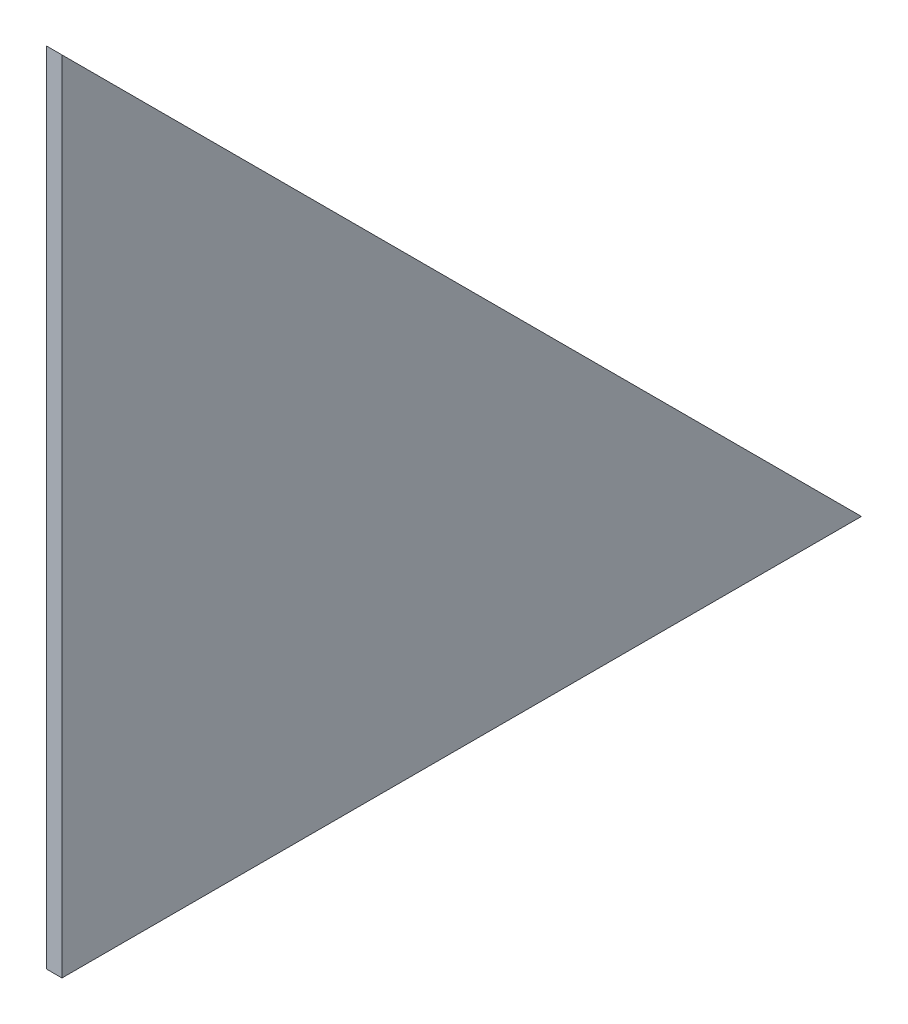
SolidWorks part; units mm, degrees
material "Balsa"
ref_plane "Front Plane" through (0, 0, 0) normal (0, 0, 1) x (1, 0, 0)
ref_plane "Top Plane" through (0, 0, 0) normal (0, 1, 0) x (1, 0, 0)
ref_plane "Right Plane" through (0, 0, 0) normal (1, 0, 0) x (0, 0, -1)
sketch "Sketch1" plane through (0, 0, 0) normal (1, 0, 0) x (0, 0, -1)
  line L0 (0, 0) -> (0, 165.1)
  line L1 (0, 165.1) -> (165.1, 0)
  line L2 (165.1, 0) -> (0, 0)
  dimension "D1" = 233.4867
  dimension "D2" = 45
extrude "Boss-Extrude1" add sketch "Sketch1" along normal blind 3.175
